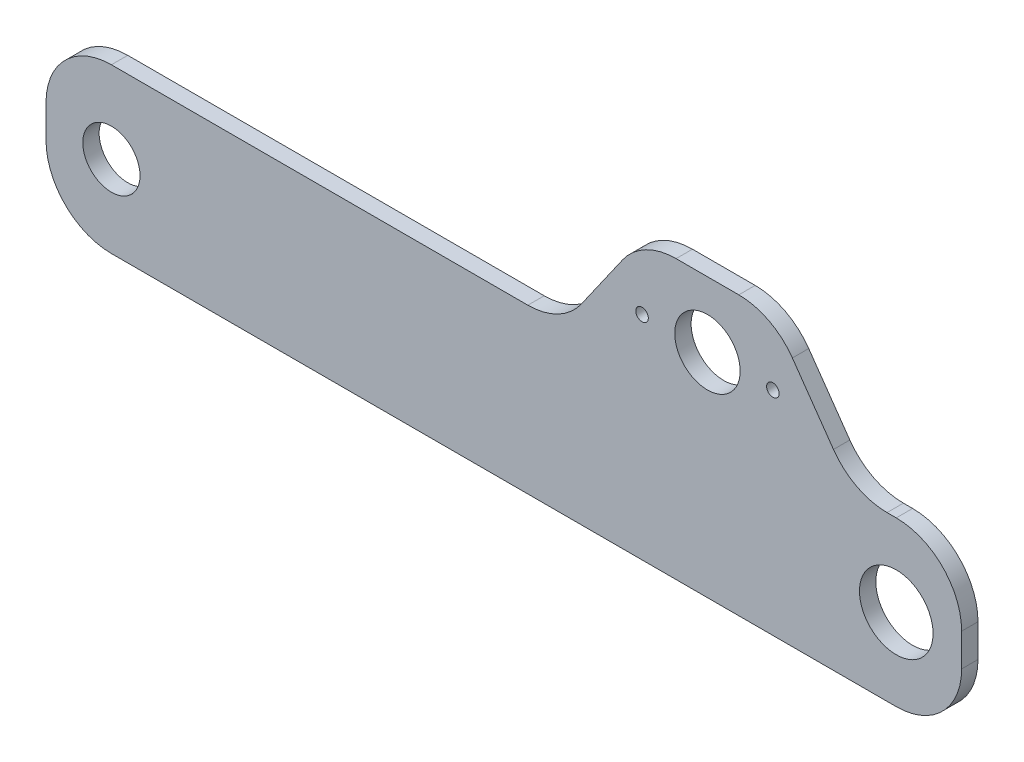
SolidWorks part; units mm, degrees
material "ABS PC"
ref_plane "Front Plane" through (0, 0, 0) normal (0, 0, 1) x (1, 0, 0)
ref_plane "Top Plane" through (0, 0, 0) normal (0, 1, 0) x (1, 0, 0)
ref_plane "Right Plane" through (0, 0, 0) normal (1, 0, 0) x (0, 0, -1)
sketch "Layout" plane through (0, 0, 0) normal (0, 0, 1) x (1, 0, 0)
  line L0 (-329.0442, 0) -> (309.3606, 0) construction
  line L1 (36.9648, 44.45) -> (341.7648, 44.45)
  line L2 (11.5648, 69.85) -> (11.5648, 82.55)
  line L3 (36.9648, 107.95) -> (198.6989, 107.95)
  line L4 (367.1648, 69.85) -> (367.1648, 82.55)
  line L8 (11.5648, 76.2) -> (367.1648, 76.2) construction
  line L9 (243.0455, 127) -> (293.8455, 127) construction
  line L10 (219.5053, 118.7812) -> (235.4614, 141.5688)
  line L11 (256.2679, 152.4) -> (280.6231, 152.4)
  line L12 (301.4296, 141.5688) -> (317.3857, 118.7812)
  line L14 (338.1921, 107.95) -> (341.7648, 107.95)
  circle A0 centre (36.9648, 76.2) radius 11.1125
  circle A1 centre (341.7648, 76.2) radius 14.2875
  circle A3 centre (268.4455, 127) radius 25.4 construction
  circle A4 centre (243.0455, 127) radius 2.4384
  circle A5 centre (293.8455, 127) radius 2.4384
  circle A6 centre (341.7648, 76.2) radius 38.1 construction
  circle A7 centre (268.4455, 127) radius 12.7
  arc A8 (341.7648, 44.45) -> (367.1648, 69.85) centre (341.7648, 69.85) ccw
  arc A9 (341.7648, 107.95) -> (367.1648, 82.55) centre (341.7648, 82.55) cw
  arc A10 (317.3857, 118.7812) -> (338.1921, 107.95) centre (338.1921, 133.35) ccw
  arc A11 (280.6231, 152.4) -> (301.4296, 141.5688) centre (280.6231, 127) cw
  arc A12 (235.4614, 141.5688) -> (256.2679, 152.4) centre (256.2679, 127) cw
  arc A13 (219.5053, 118.7812) -> (198.6989, 107.95) centre (198.6989, 133.35) cw
  arc A14 (36.9648, 44.45) -> (11.5648, 69.85) centre (36.9648, 69.85) cw
  arc A15 (11.5648, 82.55) -> (36.9648, 107.95) centre (36.9648, 82.55) cw
  point P6 (0, 0)
  point P8 (0, 0)
  point P31 (367.1648, 107.95)
  point P34 (324.9697, 107.95)
  point P37 (293.8455, 152.4)
  point P40 (243.0455, 152.4)
  point P47 (11.5648, 107.95)
  dimension "D9" = 22.225
  dimension "D10" = 28.575
  dimension "D11" = 76.2
  dimension "D12" = 50.8
  dimension "D15" = 4.8768
  dimension "D16" = 25.4
  dimension "D4" = 25.4
  dimension "D2" = 63.5
  dimension "D3" = 355.6
  dimension "D8" = 25.4
  dimension "D13" = 89.1984
  dimension "D14" = 25.4
  dimension "D17" = 50.8
  dimension "D18" = 44.45
  dimension "D19" = 235
  dimension "D20" = 25.4
  dimension "D21" = 50.8
extrude "Boss-Extrude1" add sketch "Layout" along normal blind 6.35
